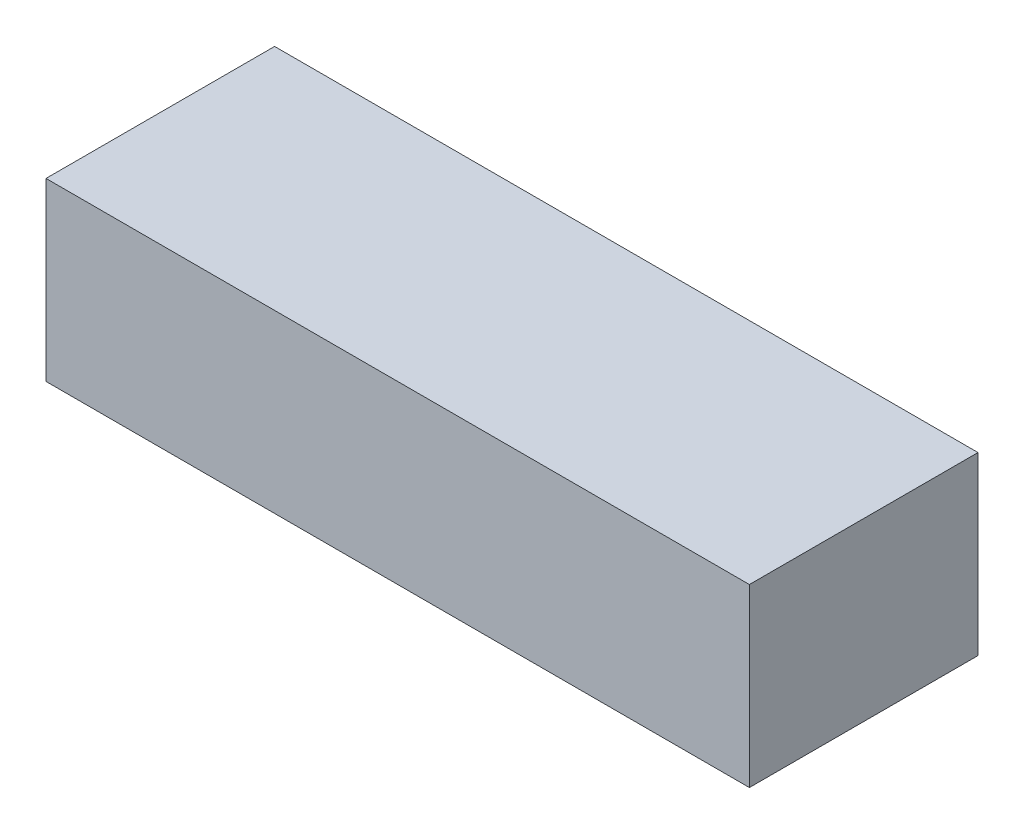
SolidWorks part; units mm, degrees
ref_plane "Front Plane" through (0, 0, 0) normal (0, 0, 1) x (1, 0, 0)
ref_plane "Top Plane" through (0, 0, 0) normal (0, 1, 0) x (1, 0, 0)
ref_plane "Right Plane" through (0, 0, 0) normal (1, 0, 0) x (0, 0, -1)
sketch "Sketch1" plane through (0, 0, 0) normal (0, 1, 0) x (1, 0, 0)
  line L1 (0, 0) -> (40, 0)
  line L2 (0, 0) -> (0, 13)
  line L3 (0, 13) -> (40, 13)
  line L4 (40, 0) -> (40, 13)
extrude "Boss-Extrude1" add sketch "Sketch1" along normal blind 10
